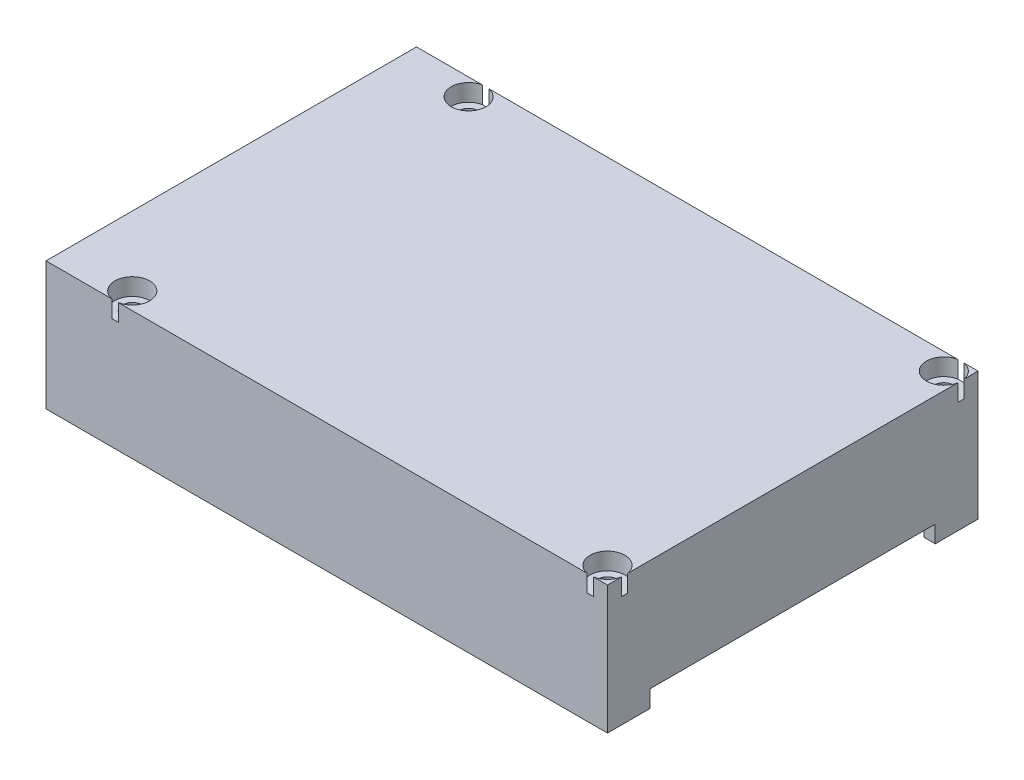
SolidWorks part; units mm, degrees
ref_plane "前视基准面" through (0, 0, 0) normal (0, 0, 1) x (1, 0, 0)
ref_plane "上视基准面" through (0, 0, 0) normal (0, 1, 0) x (1, 0, 0)
ref_plane "右视基准面" through (0, 0, 0) normal (1, 0, 0) x (0, 0, -1)
sketch "草图1" plane through (0, 0, 0) normal (0, 1, 0) x (1, 0, 0)
  line L1 (-49.25, 32.5) -> (49.25, 32.5)
  line L2 (-49.25, 32.5) -> (-49.25, -32.5)
  line L3 (-49.25, -32.5) -> (49.25, -32.5)
  line L4 (49.25, 32.5) -> (49.25, -32.5)
  line L5 (-49.25, 32.5) -> (49.25, -32.5) construction
  line L6 (-49.25, -32.5) -> (49.25, 32.5) construction
  point P0 (0, 0)
  dimension "D1" = 98.5
  dimension "D2" = 65
extrude "凸台-拉伸1" add sketch "草图1" along normal blind 3.5
ref_plane "基准面1" through (0, 0, 0) normal (0, -1, 0) x (-1, 0, 0)
sketch "草图2" plane through (0, 0, 0) normal (0, -1, 0) x (-1, 0, 0)
  line L0 (49.25, 32.5) -> (49.25, -32.5) construction
  line L1 (-47.25, 31) -> (47.25, 31)
  line L2 (-47.25, 31) -> (-47.25, -31)
  line L3 (-47.25, -31) -> (47.25, -31)
  line L4 (47.25, 31) -> (47.25, -31)
  line L5 (-47.25, 31) -> (47.25, -31) construction
  line L6 (-47.25, -31) -> (47.25, 31) construction
  line L7 (49.25, -32.5) -> (-49.25, -32.5) construction
  line L9 (-49.25, 32.5) -> (49.25, 32.5)
  line L10 (-49.25, 32.5) -> (-49.25, -32.5)
  line L11 (-49.25, -32.5) -> (49.25, -32.5)
  line L12 (49.25, 32.5) -> (49.25, -32.5)
  point P0 (0, 0)
  dimension "D1" = 2
  dimension "D2" = 1.5
extrude "凸台-拉伸2" add sketch "草图2" along normal blind 19
ref_plane "基准面2" through (-49.25, 0, 0) normal (-1, 0, 0) x (0, 0, 1)
ref_plane "基准面3" through (0, 3.5, 0) normal (0, 1, 0) x (1, 0, 0)
ref_plane "基准面4" through (0, -19, 0) normal (0, -1, 0) x (-1, 0, 0)
sketch "草图9" plane through (0, 3.5, 0) normal (0, 1, 0) x (1, 0, 0)
  line L0 (49.25, -32.5) -> (49.25, 32.5) construction
  line L1 (49.25, 32.5) -> (-49.25, 32.5) construction
  line L2 (-49.25, -32.5) -> (49.25, -32.5) construction
  circle A0 centre (46.25, 29.5) radius 1.75
  circle A1 centre (46.25, -29.5) radius 1.75
  circle A2 centre (-37.117, 29.5) radius 1.75
  circle A3 centre (-37.117, -29.5) radius 1.75
  dimension "D1" = 3.5
  dimension "D4" = 3.5
  dimension "D5" = 3
  dimension "D8" = 3.5
  dimension "D9" = 3.5
  dimension "D2" = 3
  dimension "D3" = 3
  dimension "D6" = 3
  dimension "D7" = 83.367
extrude "切除-拉伸7" cut sketch "草图9" against normal through all
ref_plane "基准面6" through (0, 0, 0) normal (0, -1, 0) x (-1, 0, 0)
sketch "草图10" plane through (0, 0, 0) normal (0, -1, 0) x (-1, 0, 0)
  circle A0 centre (-46.25, 29.5) radius 1.75
  circle A1 centre (-46.25, 29.5) radius 2.25
  circle A2 centre (37.117, 29.5) radius 1.75
  circle A3 centre (37.117, 29.5) radius 2.25
  circle A4 centre (-46.25, -29.5) radius 1.75
  circle A5 centre (-46.25, -29.5) radius 2.25
  circle A6 centre (37.117, -29.5) radius 1.75
  circle A7 centre (37.117, -29.5) radius 2.25
  dimension "D1" = 4.5
  dimension "D2" = 4.5
  dimension "D3" = 3.5
  dimension "D4" = 3.5
  dimension "D5" = 4.5
  dimension "D6" = 3.5
  dimension "D7" = 4.5
extrude "凸台-拉伸6" add sketch "草图10" along normal through all
sketch "草图11" plane through (0, -19, 0) normal (0, -1, 0) x (-1, 0, 0)
  line L1 (49.25, 32.5) -> (40.75, 32.5)
  line L2 (49.25, 32.5) -> (49.25, 16.6)
  line L3 (49.25, 16.6) -> (40.75, 16.6)
  line L4 (40.75, 32.5) -> (40.75, 16.6)
  dimension "D1" = 15.9
  dimension "D2" = 8.5
extrude "切除-拉伸8" cut sketch "草图11" against normal blind 7
ref_plane "基准面7" through (49.25, 0, 0) normal (1, 0, 0) x (0, 0, -1)
sketch "草图12" plane through (49.25, 0, 0) normal (1, 0, 0) x (0, 0, -1)
  line L0 (32.5, -19) -> (-32.5, -19) construction
  line L1 (-25, -16) -> (25, -16)
  line L2 (-25, -16) -> (-25, -22)
  line L3 (-25, -22) -> (25, -22)
  line L4 (25, -16) -> (25, -22)
  line L5 (-25, -16) -> (25, -22) construction
  line L6 (-25, -22) -> (25, -16) construction
  point P0 (0, -19)
  dimension "D1" = 50
  dimension "D2" = 6
extrude "切除-拉伸9" cut sketch "草图12" against normal blind 7
sketch "草图13" plane through (0, 3.5, 0) normal (0, 1, 0) x (1, 0, 0)
  circle A0 centre (-37.117, 29.5) radius 3.05
  circle A1 centre (46.25, 29.5) radius 3.05
  circle A2 centre (46.25, -29.5) radius 3.05
  circle A3 centre (-37.117, -29.5) radius 3.05
  dimension "D1" = 6.1
  dimension "6" = 6.1
  dimension "D2" = 6.1
  dimension "D3" = 6.1
extrude "切除-拉伸10" cut sketch "草图13" against normal blind 3
